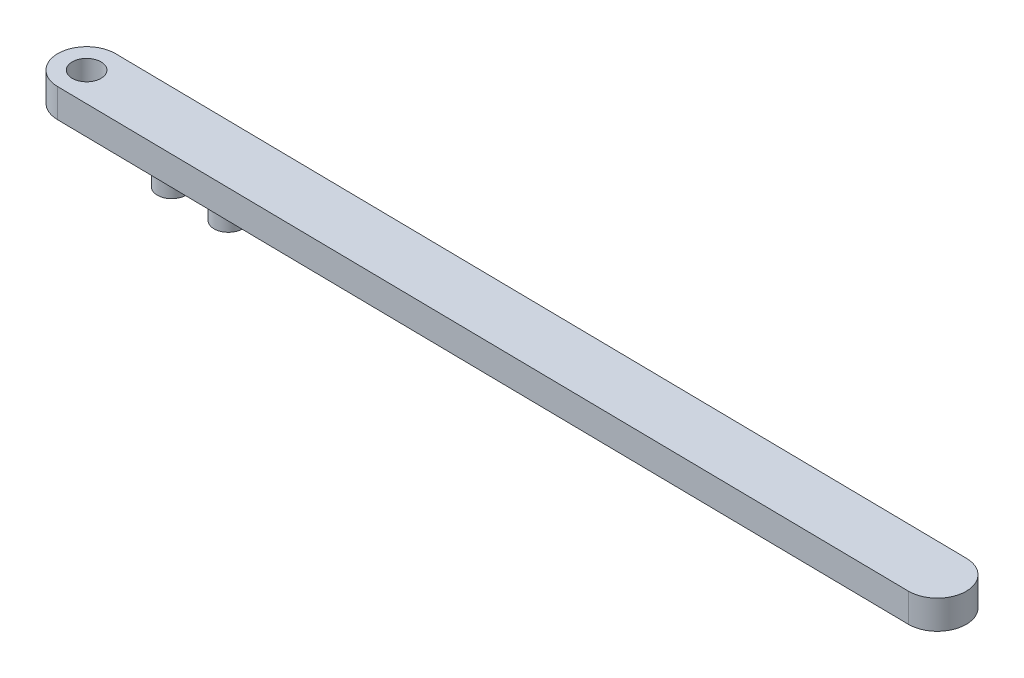
SolidWorks part; units mm, degrees
ref_plane "Front Plane" through (0, 0, 0) normal (0, 0, 1) x (1, 0, 0)
ref_plane "Top Plane" through (0, 0, 0) normal (0, 1, 0) x (1, 0, 0)
ref_plane "Right Plane" through (0, 0, 0) normal (1, 0, 0) x (0, 0, -1)
sketch "Sketch1" plane through (0, 0, 0) normal (0, 1, 0) x (1, 0, 0)
  line L0 (-14.5716, 1.7071) -> (135.4284, -0.3082) construction
  line L1 (-14.5044, 6.7067) -> (135.4956, 4.6913)
  line L2 (-14.6388, -3.2924) -> (135.3612, -5.3078)
  arc A0 (-14.5044, 6.7067) -> (-14.6388, -3.2924) centre (-14.5716, 1.7071) ccw
  arc A1 (135.3612, -5.3078) -> (135.4956, 4.6913) centre (135.4284, -0.3082) ccw
  circle A2 centre (-14.5716, 1.7071) radius 2.5
  point P2 (60.4284, 0.6995)
  dimension "D2" = 5
  dimension "D1" = 150
  dimension "D3" = 10
  dimension "D4" = 0
extrude "Boss-Extrude1" add sketch "Sketch1" along normal blind 5
sketch "Sketch2" plane through (0, 5, 0) normal (0, 1, 0) x (1, 0, 0)
  line L0 (-14.6388, -3.2924) -> (135.3612, -5.3078) construction
  circle A0 centre (0.4284, 1.5056) radius 2.5
  circle A1 centre (-14.5716, 1.7071) radius 2.5 construction
  circle A2 centre (10.4284, 1.3713) radius 2.5
  dimension "D2" = 5
  dimension "D5" = 5
  dimension "D1" = 15
  dimension "D3" = 5
  dimension "D4" = 10
  dimension "D6" = 5
extrude "Boss-Extrude2" add sketch "Sketch2" against normal blind 10
